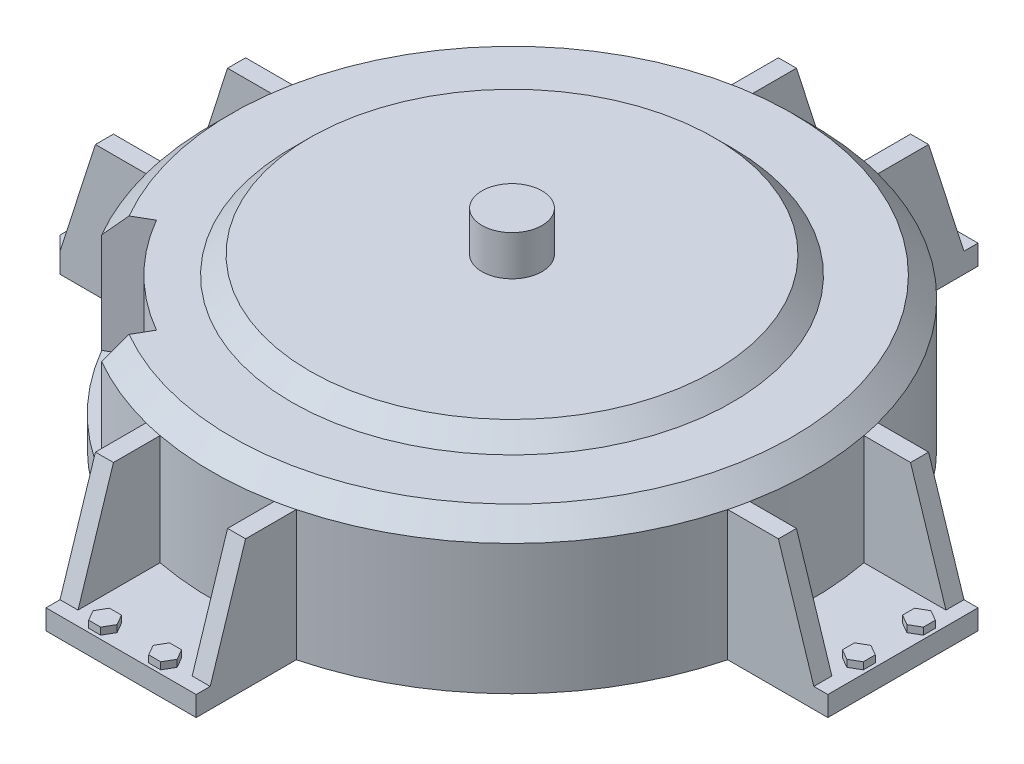
SolidWorks part; units mm, degrees
ref_plane "Front Plane" through (0, 0, 0) normal (0, 0, 1) x (1, 0, 0)
ref_plane "Top Plane" through (0, 0, 0) normal (0, 1, 0) x (1, 0, 0)
ref_plane "Right Plane" through (0, 0, 0) normal (1, 0, 0) x (0, 0, -1)
sketch "Sketch1" plane through (0, 0, 0) normal (0, 1, 0) x (1, 0, 0)
  circle A0 centre (0, 0) radius 150
  dimension "D1" = 300
extrude "Boss-Extrude1" add sketch "Sketch1" along normal blind 75
chamfer "Chamfer1" distance 10 angle 45 1 edges at (0, 75, 150)
sketch "Sketch2" plane through (0, 75, 0) normal (0, 1, 0) x (1, 0, 0)
  line L0 (0, 0) -> (-247.3625, 0) construction
  line L1 (-145.2369, 37.5) -> (-195.2369, 37.5)
  line L2 (-195.2369, 37.5) -> (-195.2369, -37.5)
  line L3 (-195.2369, -37.5) -> (-145.2369, -37.5)
  circle A0 centre (0, 0) radius 150 construction
  arc A1 (-145.2369, 37.5) -> (-145.2369, -37.5) centre (0, 0) ccw
  dimension "D1" = 75
  dimension "D2" = 50
extrude "Boss-Extrude2" add sketch "Sketch2" along normal blind 10 from offset 75 offset against normal yes
chamfer "Chamfer2" distance 7 angle 45 2 edges at (-195.2369, 5, -37.5) (-195.2369, 5, 37.5)
sketch "Sketch3" plane through (0, 0, 37.5) normal (0, 0, 1) x (1, 0, 0)
  line L0 (-145.2369, 10) -> (-145.2369, 65)
  line L1 (-150, 65) -> (150, 65) construction
  line L2 (-145.2369, 65) -> (-170.5569, 65)
  line L3 (-170.5569, 65) -> (-188.2369, 10)
  line L4 (-188.2369, 10) -> (-145.2369, 10)
  dimension "D1" = 17.68
  dimension "D2" = 25.32
extrude "Boss-Extrude3" add sketch "Sketch3" against normal blind 9
sketch "Sketch4" plane through (0, 10, 0) normal (0, 1, 0) x (1, 0, 0)
  line L0 (-150, 0) -> (-233.2345, 0) construction
  line L1 (-188.2369, 37.5) -> (-188.2369, -37.5) construction
  line L3 (-183.0407, -12) -> (-188.2369, -9)
  line L4 (-188.2369, -9) -> (-193.433, -12)
  line L5 (-193.433, -12) -> (-193.433, -18)
  line L6 (-193.433, -18) -> (-188.2369, -21)
  line L7 (-188.2369, -21) -> (-183.0407, -18)
  line L8 (-183.0407, -18) -> (-183.0407, -12)
  arc A1 (-145.2369, 37.5) -> (-147.2676, -28.5) centre (0, 0) ccw construction
  circle A2 centre (-188.2369, -15) radius 5.1962 construction
  dimension "D1" = 6
  dimension "D2" = 13.5
extrude "Boss-Extrude4" add sketch "Sketch4" along normal blind 3.5
mirror "Mirror1" about plane through (0, 0, 0) normal (0, 0, 1) of "Boss-Extrude4", "Boss-Extrude3"
pattern_circular "CirPattern1" count 4 every 90 about axis through (0, 0, 0) along (0, 1, 0) of "Boss-Extrude2", "Boss-Extrude4", "Mirror1", "Boss-Extrude3"
sketch "Sketch5" plane through (0, 75, 0) normal (0, 1, 0) x (1, 0, 0)
  line L0 (257.6741, 0) -> (-328.7566, 0) construction
  line L1 (0, -242.0776) -> (0, 234.3408) construction
  line L2 (-112.5833, -65) -> (-129.9038, -75)
  line L3 (-65, -112.5833) -> (-75, -129.9038)
  arc A0 (-112.5833, -65) -> (-65, -112.5833) centre (0, 0) ccw
  circle A1 centre (0, 0) radius 140 construction
  circle A2 centre (0, 0) radius 140
  arc A3 (0, -130) -> (-130, 0) centre (0, 0) ccw
  arc A4 (-145.2369, -37.5) -> (-37.5, -145.2369) centre (0, 0) ccw construction
  arc A5 (-129.9038, -75) -> (-75, -129.9038) centre (0, 0) ccw
  arc A6 (-129.9038, -75) -> (-75, -129.9038) centre (0, 0) ccw
  circle M7 centre (0, 0) radius 140
  dimension "D1" = 260
  dimension "D2" = 30
  dimension "D3" = 30
extrude "Cut-Extrude1" cut sketch "Sketch5" against normal blind 60 contours A0 L2 L3 M7 | L2 A5 L3 M7
sketch "Sketch6" plane through (0, 75, 0) normal (0, 1, 0) x (1, 0, 0)
  circle A0 centre (0, 0) radius 110
  dimension "D1" = 220
extrude "Boss-Extrude5" add sketch "Sketch6" along normal blind 9 draft 45
sketch "Sketch7" plane through (0, 84, 0) normal (0, 1, 0) x (1, 0, 0)
  circle A0 centre (0, 0) radius 15
  dimension "D1" = 30
extrude "Boss-Extrude6" add sketch "Sketch7" along normal blind 20
